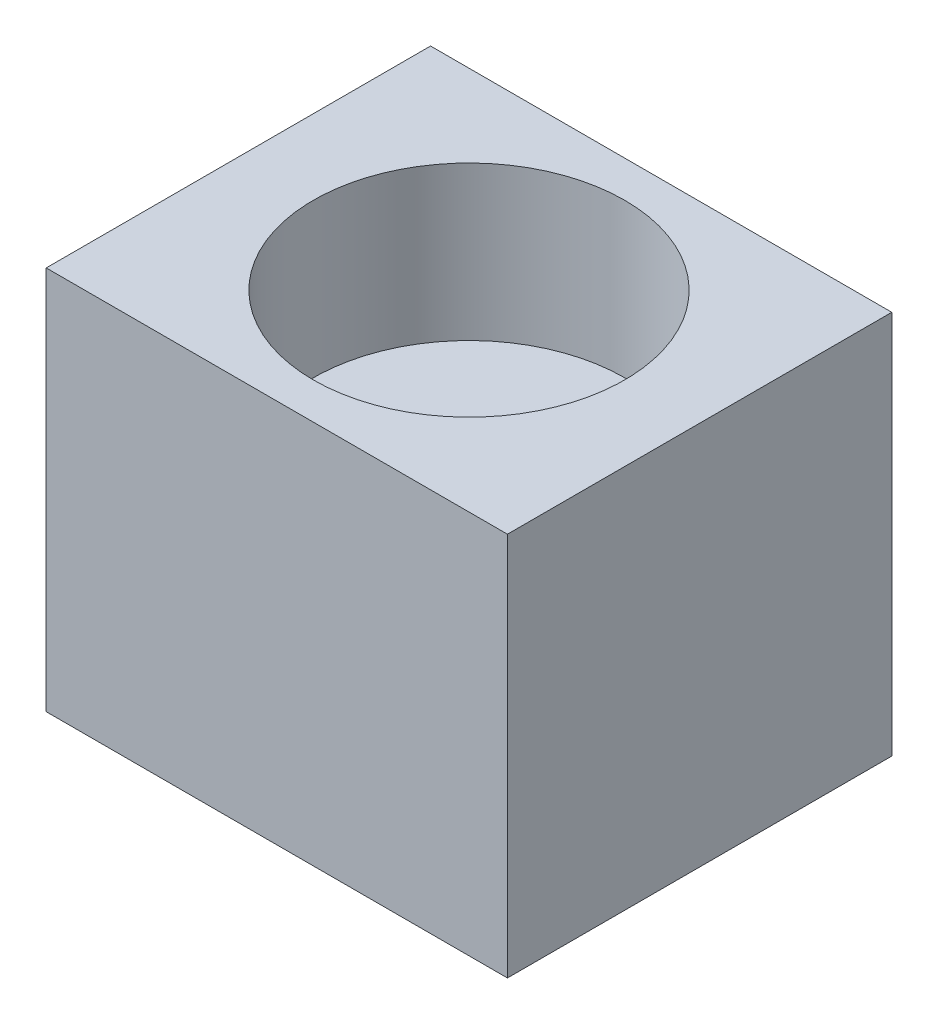
SolidWorks part; units mm, degrees
ref_plane "Front Plane" through (0, 0, 0) normal (0, 0, 1) x (1, 0, 0)
ref_plane "Top Plane" through (0, 0, 0) normal (0, 1, 0) x (1, 0, 0)
ref_plane "Right Plane" through (0, 0, 0) normal (1, 0, 0) x (0, 0, -1)
sketch "Sketch1" plane through (0, 0, 0) normal (0, 1, 0) x (1, 0, 0)
  line L1 (-30, -25) -> (30, -25)
  line L2 (-30, -25) -> (-30, 25)
  line L3 (-30, 25) -> (30, 25)
  line L4 (30, -25) -> (30, 25)
  line L5 (-30, -25) -> (30, 25) construction
  line L6 (-30, 25) -> (30, -25) construction
  point P0 (0, 0)
  dimension "D1" = 60
  dimension "D2" = 50
extrude "Boss-Extrude2" add sketch "Sketch1" along normal blind 50
sketch "Sketch4" plane through (0, 50, 0) normal (0, 1, 0) x (1, 0, 0)
  circle A0 centre (0, 0) radius 20.25
  dimension "D1" = 40.5
extrude "Cut-Extrude1" cut sketch "Sketch4" against normal blind 20
